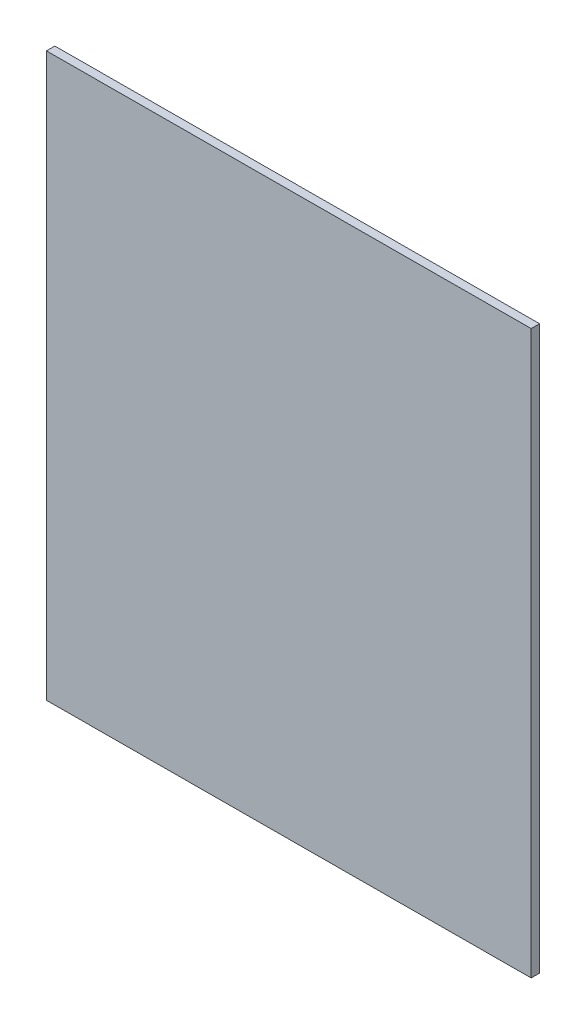
SolidWorks part; units mm, degrees
ref_plane "Front Plane" through (0, 0, 0) normal (0, 0, 1) x (1, 0, 0)
ref_plane "Top Plane" through (0, 0, 0) normal (0, 1, 0) x (1, 0, 0)
ref_plane "Right Plane" through (0, 0, 0) normal (1, 0, 0) x (0, 0, -1)
ref_plane "Plane1" through (-0.0853, 0, -21.9977) normal (0.0039, 0, 1) x (1, 0, -0.0039)
sketch "Sketch2" plane through (-0.0853, 0, -21.9977) normal (0.0039, 0, 1) x (1, 0, -0.0039)
  line L1 (-57.5229, 258.864) -> (-57.5229, 392.864)
  line L3 (57.5229, 258.864) -> (57.5229, 392.864)
  line L4 (-57.5229, 392.864) -> (57.5229, 392.864)
  line L5 (-57.5229, 258.864) -> (57.5229, 258.864)
extrude "Boss-Extrude1" add sketch "Sketch2" along normal blind 2
